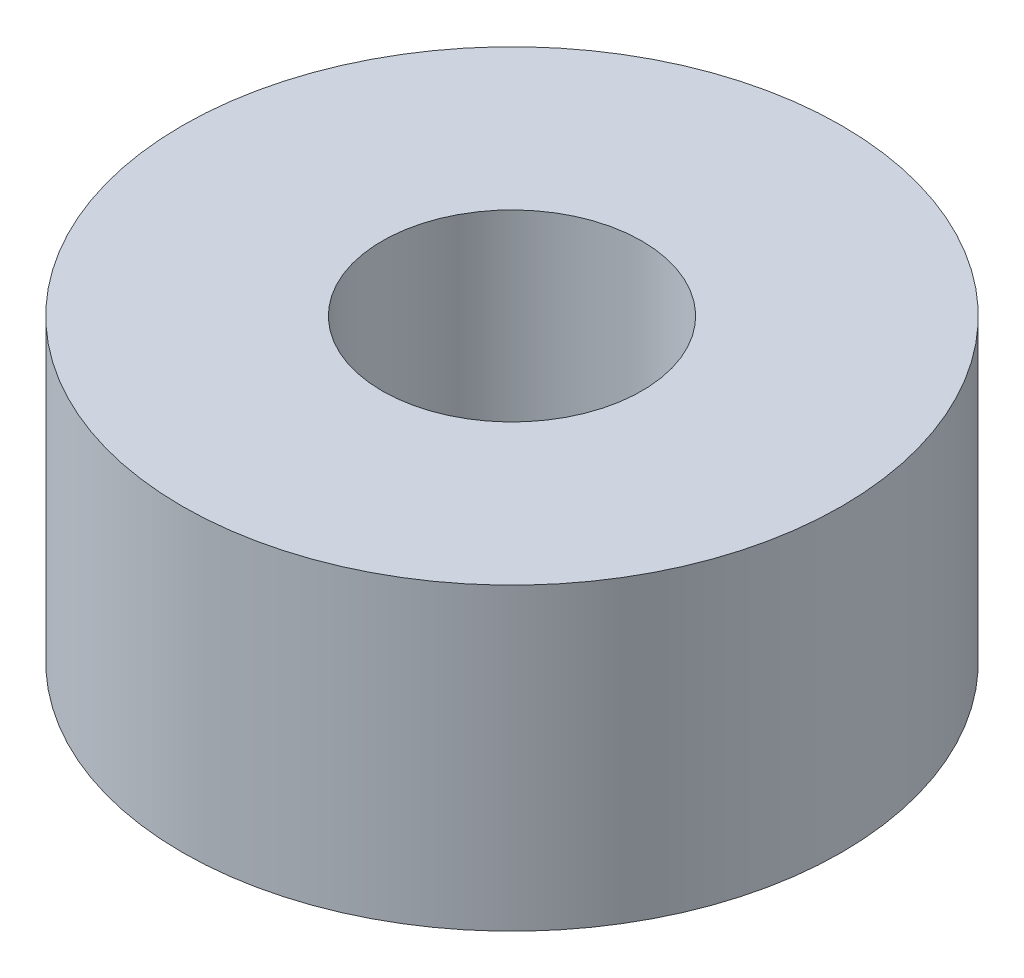
SolidWorks part; units mm, degrees
ref_plane "Front Plane" through (0, 0, 0) normal (0, 0, 1) x (1, 0, 0)
ref_plane "Top Plane" through (0, 0, 0) normal (0, 1, 0) x (1, 0, 0)
ref_plane "Right Plane" through (0, 0, 0) normal (1, 0, 0) x (0, 0, -1)
sketch "Sketch1" plane through (0, 0, 0) normal (0, 1, 0) x (1, 0, 0)
  circle A0 centre (0, 0) radius 1.3
  circle A1 centre (0, 0) radius 3.3
  dimension "D1" = 2
  dimension "D2" = 2.6
extrude "Boss-Extrude1" add sketch "Sketch1" along normal blind 3
